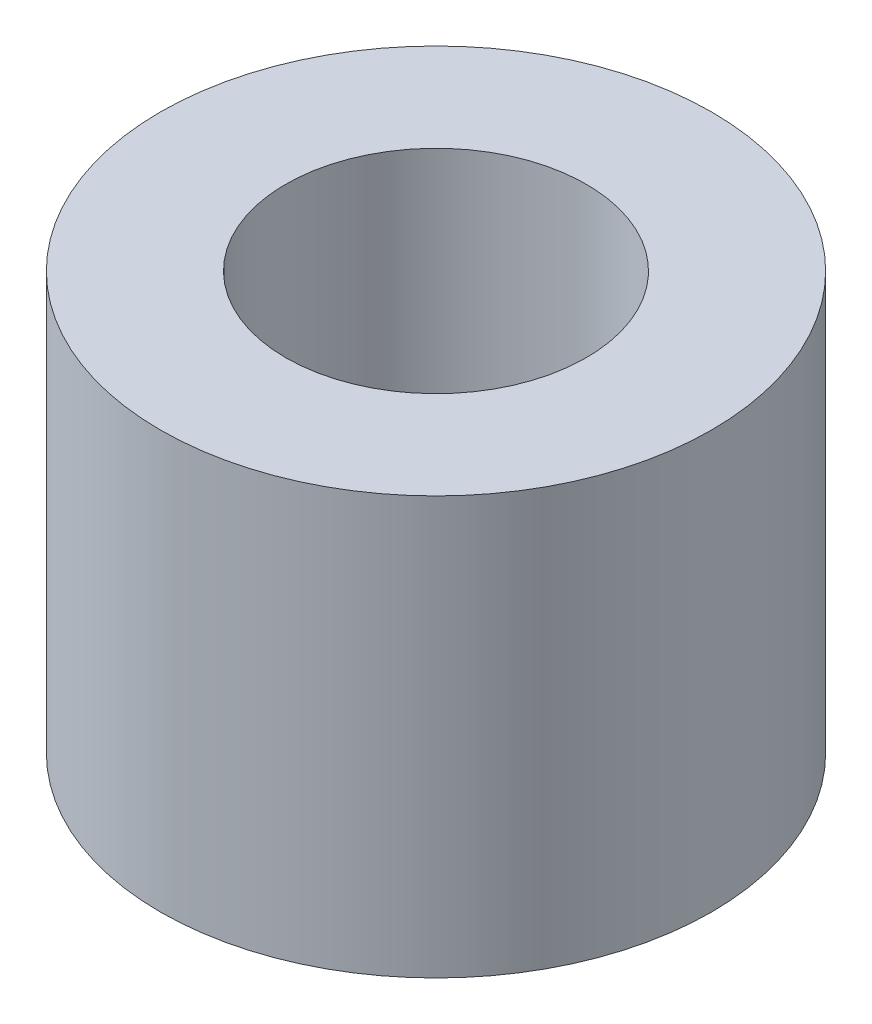
SolidWorks part; units mm, degrees
ref_plane "Front Plane" through (0, 0, 0) normal (0, 0, 1) x (1, 0, 0)
ref_plane "Top Plane" through (0, 0, 0) normal (0, 1, 0) x (1, 0, 0)
ref_plane "Right Plane" through (0, 0, 0) normal (1, 0, 0) x (0, 0, -1)
sketch "Sketch1" plane through (0, 0, 0) normal (0, 1, 0) x (1, 0, 0)
  circle A0 centre (0, 0) radius 1.8
  circle A1 centre (0, 0) radius 3.3
  dimension "D1" = 3.6
  dimension "D2" = 1.5
extrude "Boss-Extrude1" add sketch "Sketch1" along normal blind 5
